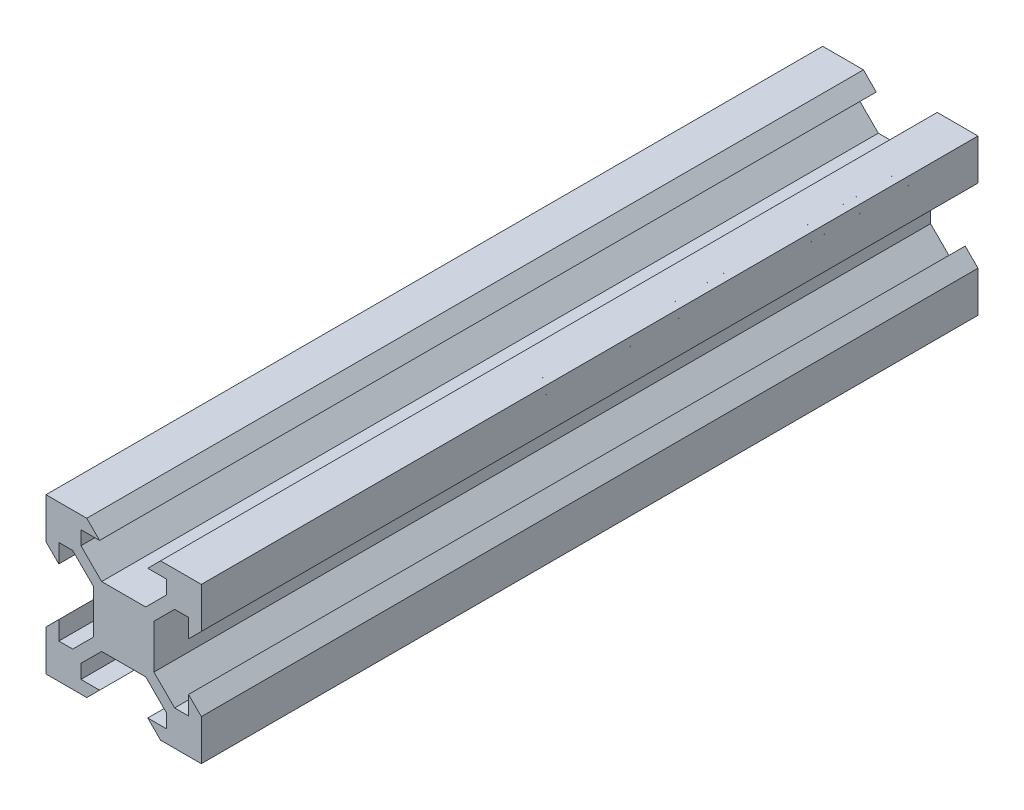
SolidWorks part; units mm, degrees
material "6061 Alloy"
ref_plane "Front Plane" through (0, 0, 0) normal (0, 0, 1) x (1, 0, 0)
ref_plane "Top Plane" through (0, 0, 0) normal (0, 1, 0) x (1, 0, 0)
ref_plane "Right Plane" through (0, 0, 0) normal (1, 0, 0) x (0, 0, -1)
sketch "Sketch1" plane through (0, 0, 0) normal (0, 0, 1) x (1, 0, 0)
  line L4 (-2.8343, 3.894) -> (2.8343, 3.894)
  line L6 (2.8343, 3.894) -> (5.5, 6.5588)
  line L7 (5.5, 6.5588) -> (5.5, 8.3491)
  line L8 (5.5, 8.3491) -> (3.1, 8.3491)
  line L11 (3.1, 8.3491) -> (4.75, 9.9986)
  line L12 (4.75, 9.9986) -> (10, 9.9986)
  line L14 (10, 9.9986) -> (10, 4.747)
  line L16 (10, 4.747) -> (8.35, 3.0975)
  line L17 (8.35, 3.0975) -> (8.3507, 5.4975)
  line L18 (8.3507, 5.4975) -> (6.5605, 5.498)
  line L19 (6.5605, 5.498) -> (3.8948, 2.8332)
  line L20 (3.8948, 2.8332) -> (3.8948, -2.8332)
  line L22 (-10, 9.9986) -> (-10, 4.747)
  line L23 (-3.8948, 2.8332) -> (-3.8948, -2.8332)
  line L24 (-6.5605, 5.498) -> (-3.8948, 2.8332)
  line L25 (-8.3507, 5.4975) -> (-6.5605, 5.498)
  line L26 (-8.35, 3.0975) -> (-8.3507, 5.4975)
  line L27 (-10, 4.747) -> (-8.35, 3.0975)
  line L28 (-4.75, 9.9986) -> (-10, 9.9986)
  line L29 (-3.1, 8.3491) -> (-4.75, 9.9986)
  line L30 (-5.5, 8.3491) -> (-3.1, 8.3491)
  line L31 (-5.5, 6.5588) -> (-5.5, 8.3491)
  line L32 (-2.8343, 3.894) -> (-5.5, 6.5588)
  line L33 (-2.8343, -3.894) -> (-5.5, -6.5588)
  line L34 (-5.5, -6.5588) -> (-5.5, -8.3491)
  line L35 (-5.5, -8.3491) -> (-3.1, -8.3491)
  line L36 (-3.1, -8.3491) -> (-4.75, -9.9986)
  line L37 (-4.75, -9.9986) -> (-10, -9.9986)
  line L38 (-10, -4.747) -> (-8.35, -3.0975)
  line L39 (-8.35, -3.0975) -> (-8.3507, -5.4975)
  line L40 (-8.3507, -5.4975) -> (-6.5605, -5.498)
  line L41 (-6.5605, -5.498) -> (-3.8948, -2.8332)
  line L42 (-10, -9.9986) -> (-10, -4.747)
  line L43 (6.5605, -5.498) -> (3.8948, -2.8332)
  line L44 (8.3507, -5.4975) -> (6.5605, -5.498)
  line L45 (8.35, -3.0975) -> (8.3507, -5.4975)
  line L46 (10, -4.747) -> (8.35, -3.0975)
  line L47 (10, -9.9986) -> (10, -4.747)
  line L48 (4.75, -9.9986) -> (10, -9.9986)
  line L49 (3.1, -8.3491) -> (4.75, -9.9986)
  line L50 (5.5, -8.3491) -> (3.1, -8.3491)
  line L51 (5.5, -6.5588) -> (5.5, -8.3491)
  line L52 (2.8343, -3.894) -> (5.5, -6.5588)
  line L53 (-2.8343, -3.894) -> (2.8343, -3.894)
  circle A0 centre (0, 0) radius 2.1
  point P52 (0, 3.894)
  point P53 (-3.8948, 0)
  point P54 (3.8948, 0)
  point P74 (0, -3.894)
extrude "Boss-Extrude1" add sketch "Sketch1" along normal blind 100 contours L14 L16 L17 L18 L19 L20 L43 L44 L45 L46 L47 L48 L49 L50 L51 L52 L53 L33 L34 L35 L36 L37 L42 L38 L39 L40 L41 L23 L24 L25 L26 L27 L22 L28 L29 L30 L31 L32 L4 L6 L7 L8 L11 L12
sketch "Sketch2" plane through (0, 9.9986, 0) normal (0, 1, 0) x (1, 0, 0)
  line L0 (-10, -100) -> (10, -91.7157)
  line L1 (10, -100) -> (10, 0) construction
  line L2 (-2.8343, -100) -> (2.8343, -100) construction
  line L3 (10, -91.7157) -> (10, -100)
  line L4 (10, -100) -> (-10, -100)
  dimension "D1" = 22.5
extrude "Cut-Extrude1" [suppressed] cut sketch "Sketch2" against normal through all
sketch "Sketch3" plane through (0, 9.9986, 0) normal (0, 1, 0) x (1, 0, 0)
  line L0 (-10, 0) -> (10, -8.2843)
  line L1 (10, -100) -> (10, 0) construction
  line L2 (10, -8.2843) -> (10, 0)
  line L3 (10, 0) -> (-10, 0)
  dimension "D1" = 22.5
extrude "Cut-Extrude2" [suppressed] cut sketch "Sketch3" against normal through all
